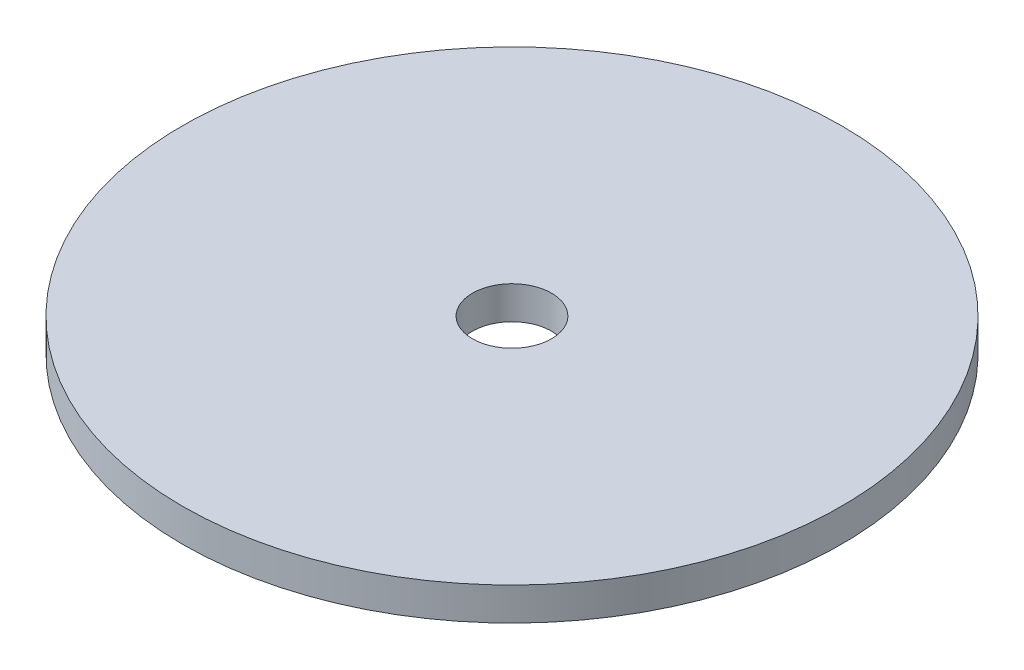
SolidWorks part; units mm, degrees
ref_plane "前视基准面" through (0, 0, 0) normal (0, 0, 1) x (1, 0, 0)
ref_plane "上视基准面" through (0, 0, 0) normal (0, 1, 0) x (1, 0, 0)
ref_plane "右视基准面" through (0, 0, 0) normal (1, 0, 0) x (0, 0, -1)
sketch "Sketch1" plane through (0, 0, 0) normal (0, 1, 0) x (1, 0, 0)
  circle A0 centre (0, 0) radius 50
  circle A1 centre (0, 0) radius 6
  dimension "D1" = 100
  dimension "D2" = 12
extrude "Boss-Extrude1" add sketch "Sketch1" along normal blind 5
